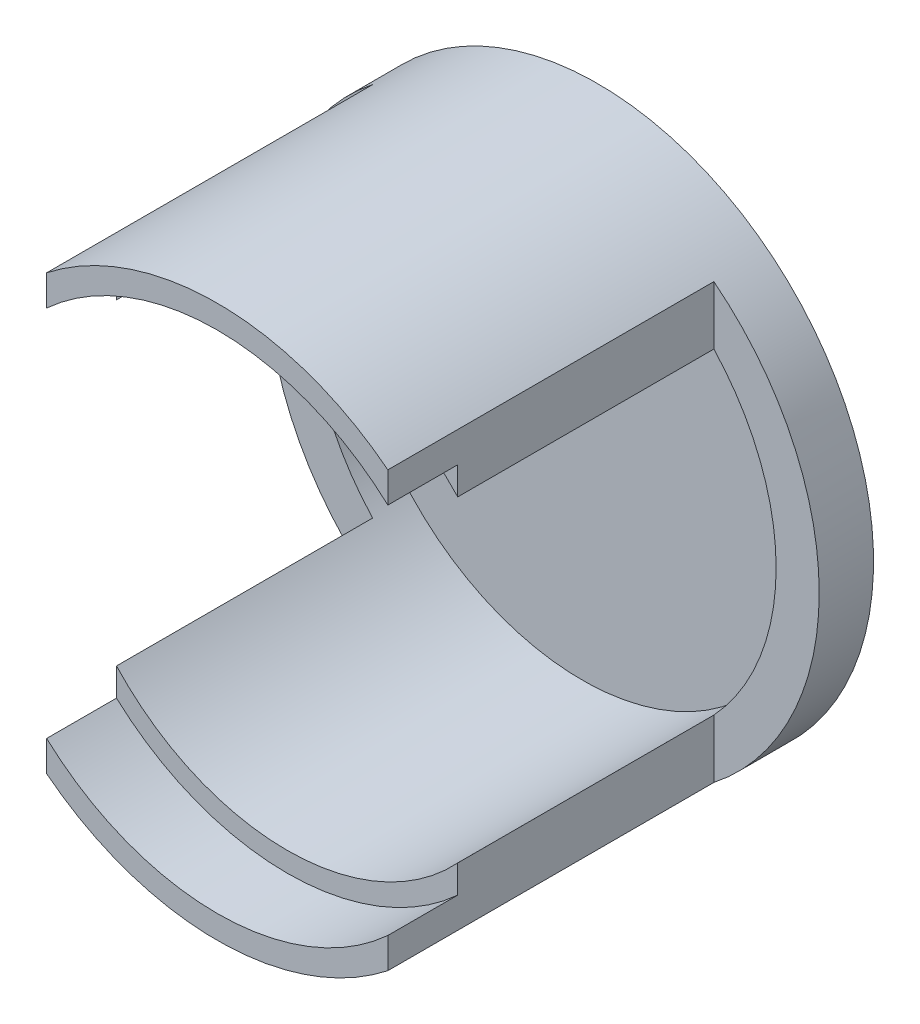
SolidWorks part; units mm, degrees
ref_plane "Front Plane" through (0, 0, 0) normal (0, 0, 1) x (1, 0, 0)
ref_plane "Top Plane" through (0, 0, 0) normal (0, 1, 0) x (1, 0, 0)
ref_plane "Right Plane" through (0, 0, 0) normal (1, 0, 0) x (0, 0, -1)
sketch "Sketch1" plane through (0, 0, 0) normal (0, 0, 1) x (1, 0, 0)
  circle A0 centre (0, 0) radius 32.55
  circle A1 centre (0, 0) radius 35.55
  dimension "D1" = 3
extrude "Boss-Extrude1" add sketch "Sketch1" along normal blind 47
sketch "Sketch2" plane through (0, 0, 0) normal (0, 0, -1) x (-1, 0, 0)
  circle A0 centre (0, 0) radius 35.55
extrude "Boss-Extrude2" add sketch "Sketch2" along normal blind 2
sketch "Sketch4" plane through (0, 0, 0) normal (0, 0, 1) x (1, 0, 0)
  circle A0 centre (0, 0) radius 30
  circle A1 centre (0, 0) radius 32.55
extrude "Boss-Extrude3" add sketch "Sketch4" along normal blind 38
sketch "Sketch5" plane through (0, 0, 47) normal (0, 0, 1) x (1, 0, 0)
  line L1 (-35.55, -35.55) -> (35.55, -35.55)
  line L2 (-35.55, -35.55) -> (-35.55, 35.55)
  line L3 (-35.55, 35.55) -> (35.55, 35.55)
  line L4 (35.55, -35.55) -> (35.55, 35.55)
  line L5 (-35.55, -35.55) -> (35.55, 35.55) construction
  line L6 (-35.55, 35.55) -> (35.55, -35.55) construction
  line L7 (-21.9801, -35.55) -> (21.9801, -35.55)
  line L8 (-21.9801, -35.55) -> (-21.9801, 35.55)
  line L9 (-21.9801, 35.55) -> (21.9801, 35.55)
  line L10 (21.9801, -35.55) -> (21.9801, 35.55)
  line L11 (-21.9801, -35.55) -> (21.9801, 35.55) construction
  line L12 (-21.9801, 35.55) -> (21.9801, -35.55) construction
  circle A0 centre (0, 0) radius 35.55
  circle M2 centre (0, 0) radius 35.55
  circle M3 centre (0, 0) radius 32.55
extrude "Cut-Extrude1" cut sketch "Sketch5" against normal blind 42 contours L8 L3 L2 M2 | L8 M2 M3 | L8 M3 | L1 L8 L2 M2 | L10 L1 L4 M2 | L10 M2 M3 | L10 M3 | L10 L4 L3 M2
fillet "Fillet1" [suppressed] radius 2
